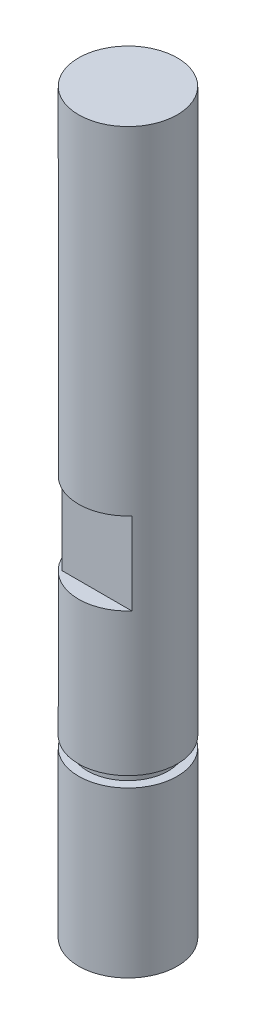
SolidWorks part; units mm, degrees
material "AISI 1020"
ref_plane "Front Plane" through (0, 0, 0) normal (0, 0, 1) x (1, 0, 0)
ref_plane "Top Plane" through (0, 0, 0) normal (0, 1, 0) x (1, 0, 0)
ref_plane "Right Plane" through (0, 0, 0) normal (1, 0, 0) x (0, 0, -1)
sketch "Sketch1" plane through (0, 0, 0) normal (0, 1, 0) x (1, 0, 0)
  circle A0 centre (0, 0) radius 3
extrude "Boss-Extrude1" add sketch "Sketch1" along normal blind 10
sketch "Sketch2" plane through (0, 10, 0) normal (0, 1, 0) x (1, 0, 0)
  circle A0 centre (0, 0) radius 2.45
  dimension "D1" = 4.9
extrude "Boss-Extrude2" add sketch "Sketch2" along normal blind 0.65
sketch "Sketch3" plane through (0, 10.65, 0) normal (0, 1, 0) x (1, 0, 0)
  circle A0 centre (0, 0) radius 3
extrude "Boss-Extrude3" add sketch "Sketch3" along normal blind 8.67
sketch "Sketch4" plane through (0, 19.32, 0) normal (0, 1, 0) x (1, 0, 0)
  line L1 (-3, -3) -> (3, -3)
  line L2 (-3, -3) -> (-3, 3)
  line L3 (-3, 3) -> (3, 3)
  line L4 (3, -3) -> (3, 3)
  line L5 (-3, -3) -> (3, 3) construction
  line L6 (-3, 3) -> (3, -3) construction
  line L7 (3, 3) -> (-2, 3)
  line L8 (3, 3) -> (3, -2)
  line L9 (3, -2) -> (-2, -2)
  line L10 (-2, 3) -> (-2, -2)
  point P0 (0, 0)
  circle M1 centre (0, 0) radius 3
extrude "Boss-Extrude4" add sketch "Sketch4" along normal blind 5 contours L10 L9 M1
sketch "Sketch5" plane through (0, 24.32, 0) normal (0, 1, 0) x (1, 0, 0)
  circle A0 centre (0, 0) radius 3
extrude "Boss-Extrude5" add sketch "Sketch5" along normal blind 20.5
